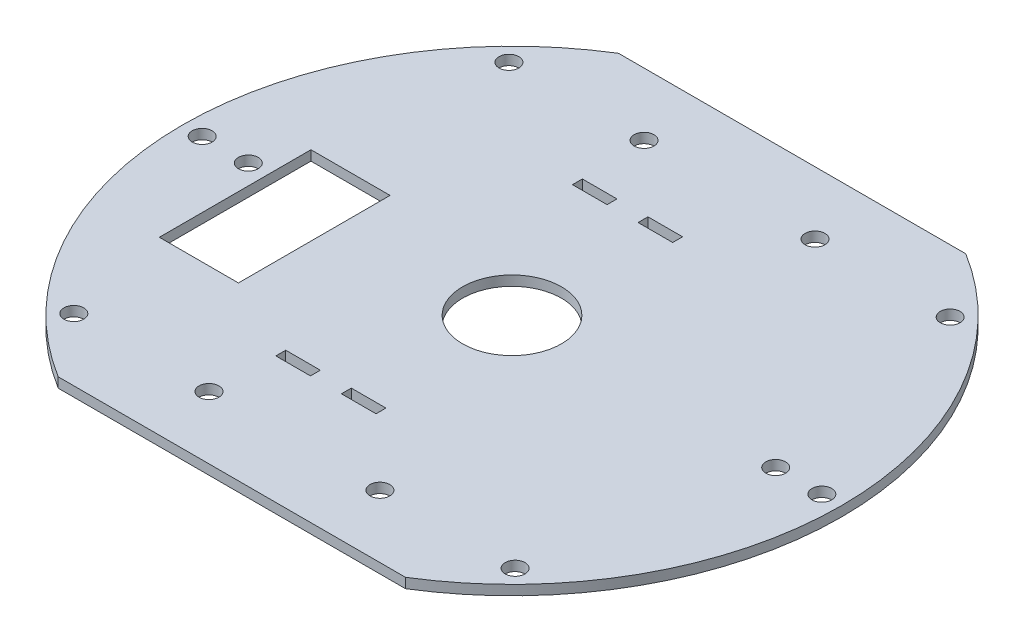
SolidWorks part; units mm, degrees
ref_plane "Front" through (0, 0, 0) normal (0, 0, 1) x (1, 0, 0)
ref_plane "Top" through (0, 0, 0) normal (0, 1, 0) x (1, 0, 0)
ref_plane "Right" through (0, 0, 0) normal (1, 0, 0) x (0, 0, -1)
sketch "Sketch2" plane through (0, 0, 0) normal (0, 1, 0) x (1, 0, 0)
  line L0 (-26.3391, 42.5) -> (26.3391, 42.5)
  line L1 (-26.3391, -42.5) -> (26.3391, -42.5)
  line L2 (-67.1283, 0) -> (65.2079, 0) construction
  arc A0 (-26.3391, 42.5) -> (-26.3391, -42.5) centre (0, 0) ccw
  arc A1 (26.3391, -42.5) -> (26.3391, 42.5) centre (0, 0) ccw
  dimension "D1" = 50
  dimension "D2" = 85
extrude "Boss-Extrude1" add sketch "Sketch2" along normal blind 1.5
sketch "Sketch3" plane through (0, 1.5, 0) normal (0, 1, 0) x (1, 0, 0)
  line L0 (0, 0) -> (96.8774, 0) construction
  line L1 (-37, 6.5) -> (-25, 6.5)
  line L2 (-37, 6.5) -> (-37, -16.5)
  line L3 (-37, -16.5) -> (-25, -16.5)
  line L4 (-25, 6.5) -> (-25, -16.5)
  line L5 (0, 0) -> (0, 97.0421) construction
  line L6 (2.625, -23.25) -> (2.625, -21.75)
  line L7 (-12.575, 23.25) -> (-7.325, 23.25)
  line L8 (-12.575, 23.25) -> (-12.575, 21.75)
  line L9 (-12.575, 21.75) -> (-7.325, 21.75)
  line L10 (-7.325, 23.25) -> (-7.325, 21.75)
  line L11 (-2.625, 23.25) -> (2.625, 23.25)
  line L12 (-2.625, 23.25) -> (-2.625, 21.75)
  line L13 (-2.625, 21.75) -> (2.625, 21.75)
  line L14 (2.625, 23.25) -> (2.625, 21.75)
  line L15 (-2.625, -21.75) -> (2.625, -21.75)
  line L16 (-2.625, -23.25) -> (-2.625, -21.75)
  line L17 (-2.625, -23.25) -> (2.625, -23.25)
  line L18 (-7.325, -23.25) -> (-7.325, -21.75)
  line L19 (-12.575, -21.75) -> (-7.325, -21.75)
  line L20 (-12.575, -23.25) -> (-12.575, -21.75)
  line L21 (-12.575, -23.25) -> (-7.325, -23.25)
  circle A0 centre (0, 0) radius 7.5
  circle A1 centre (0, 0) radius 47 construction
  circle A2 centre (-47, 0) radius 1.5
  circle A3 centre (-33.4664, 33) radius 1.5
  circle A4 centre (-12.9664, 33) radius 1.5
  circle A5 centre (-40, 0) radius 1.5
  circle A6 centre (-12.9664, -33) radius 1.5
  circle A7 centre (-33.4664, -33) radius 1.5
  circle A8 centre (33.4664, 33) radius 1.5
  circle A9 centre (12.9664, 33) radius 1.5
  circle A10 centre (12.9664, -33) radius 1.5
  circle A11 centre (33.4664, -33) radius 1.5
  circle A12 centre (40, 0) radius 1.5
  circle A13 centre (47, 0) radius 1.5
  point P42 (0, 21.75)
  dimension "D1" = 94
  dimension "D2" = 3
  dimension "D6" = 15
  dimension "D11" = 5.25
  dimension "D3" = 66
  dimension "D4" = 20.5
  dimension "D5" = 7
  dimension "D7" = 12
  dimension "D8" = 23
  dimension "D9" = 25
  dimension "D10" = 6.5
  dimension "D12" = 1.5
  dimension "D13" = 15.2
  dimension "D14" = 46.5
extrude "Cut-Extrude1" cut sketch "Sketch3" against normal through all
